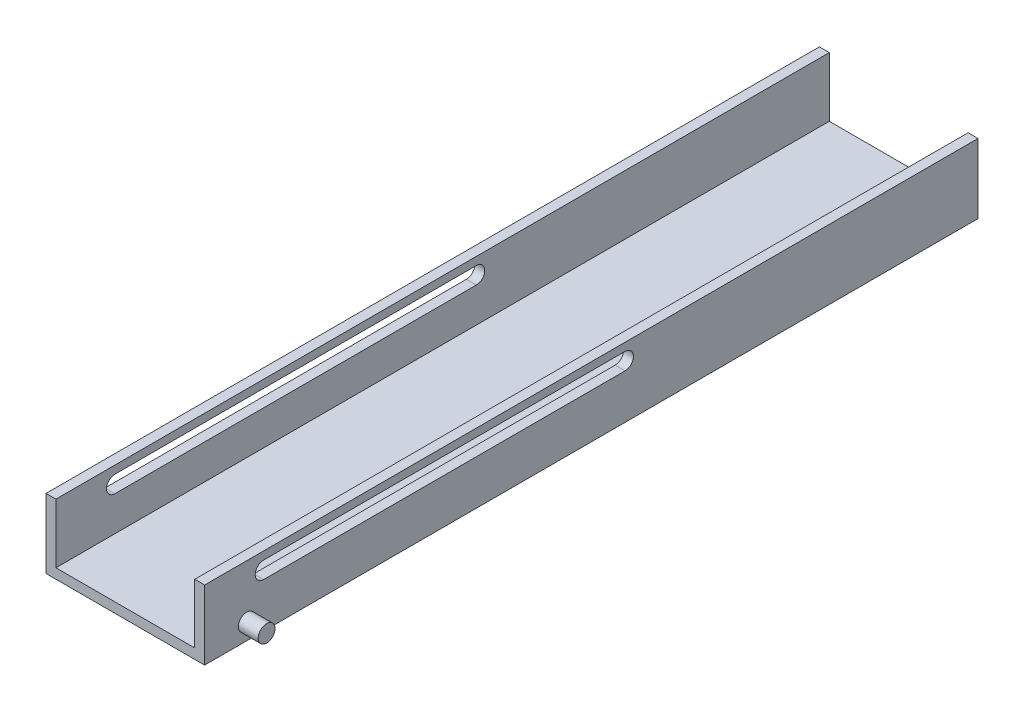
SolidWorks part; units mm, degrees
ref_plane "Front Plane" through (0, 0, 0) normal (0, 0, 1) x (1, 0, 0)
ref_plane "Top Plane" through (0, 0, 0) normal (0, 1, 0) x (1, 0, 0)
ref_plane "Right Plane" through (0, 0, 0) normal (1, 0, 0) x (0, 0, -1)
sketch "Sketch1" plane through (0, 0, 0) normal (0, 1, 0) x (1, 0, 0)
  line L1 (-20, -100) -> (20, -100)
  line L2 (-20, -100) -> (-20, 100)
  line L3 (-20, 100) -> (20, 100)
  line L4 (20, -100) -> (20, 100)
  line L5 (-20, -100) -> (20, 100) construction
  line L6 (-20, 100) -> (20, -100) construction
  point P0 (0, 0)
extrude "Boss-Extrude1" add sketch "Sketch1" along normal blind 20
sketch "Sketch2" plane through (20, 0, 0) normal (1, 0, 0) x (0, 0, -1)
  line L2 (100, 0) -> (100, 2)
  line L3 (100, 20) -> (100, 0) construction
  line L6 (100, 2) -> (100, 6.25)
  circle A2 centre (-95.75, 4.125) radius 2.125
extrude "Boss-Extrude2" add sketch "Sketch2" along normal blind 5 contours A2
sketch "Sketch3" plane through (-20, 0, 0) normal (-1, 0, 0) x (0, 0, 1)
  circle A0 centre (95.75, 4.125) radius 2.125
extrude "Boss-Extrude3" add sketch "Sketch3" along normal blind 5
sketch "Sketch4" plane through (0, 0, 100) normal (0, 0, 1) x (1, 0, 0)
  line L0 (-20, 20) -> (20, 20) construction
  line L1 (-17.5, 37.5) -> (17.5, 37.5)
  line L2 (-17.5, 37.5) -> (-17.5, 2.5)
  line L3 (-17.5, 2.5) -> (17.5, 2.5)
  line L4 (17.5, 37.5) -> (17.5, 2.5)
  line L5 (-17.5, 37.5) -> (17.5, 2.5) construction
  line L6 (-17.5, 2.5) -> (17.5, 37.5) construction
  point P0 (0, 20)
extrude "Cut-Extrude1" cut sketch "Sketch4" against normal blind 210.5
sketch "Sketch5" plane through (-20, 0, 0) normal (-1, 0, 0) x (0, 0, 1)
  line L1 (100, 0) -> (-95, 0)
  line L2 (100, 0) -> (100, 17.5)
  line L3 (100, 17.5) -> (-95, 17.5)
  line L4 (-95, 0) -> (-95, 17.5)
  line L5 (100, 0) -> (-100, 0)
  line L6 (100, 0) -> (100, 20)
  line L7 (100, 20) -> (-100, 20)
  line L8 (-100, 0) -> (-100, 20)
  line M6 (-100, 0) -> (100, 0)
  line M7 (100, 0) -> (100, 20)
  line M8 (100, 20) -> (-100, 20)
  line M9 (-100, 20) -> (-100, 0)
extrude "Cut-Extrude2" cut sketch "Sketch5" against normal blind 210.5 contours L4 L3 M6 M7 M8 M9
sketch "Sketch6" plane through (-20, 0, 0) normal (-1, 0, 0) x (0, 0, 1)
  line L5 (-90.75, 15.5) -> (95.75, 15.5)
  line L7 (-90.75, 11.25) -> (95.75, 11.25)
  arc A2 (-90.75, 15.5) -> (-90.75, 11.25) centre (-90.75, 13.375) ccw
  arc A5 (95.75, 11.25) -> (95.75, 15.5) centre (95.75, 13.375) ccw
extrude "Cut-Extrude3" cut sketch "Sketch6" against normal blind 210.5
sketch "Sketch7" plane through (-20, 0, 0) normal (-1, 0, 0) x (0, 0, 1)
  line L3 (-95, 0) -> (-95, 17.5) construction
  line L4 (6.75, 11.25) -> (-95, 11.25)
  line L6 (6.75, 15.5) -> (-95, 15.5)
  line L7 (-95, 11.25) -> (-95, 15.5)
  arc A2 (6.75, 15.5) -> (6.75, 11.25) centre (6.75, 13.375) ccw
extrude "Boss-Extrude4" add sketch "Sketch7" against normal blind 40
sketch "Sketch8" plane through (0, 0, -95) normal (0, 0, -1) x (-1, 0, 0)
  line L1 (-17.5, 11.25) -> (17.5, 11.25)
  line L2 (-17.5, 11.25) -> (-17.5, 15.5)
  line L3 (-17.5, 15.5) -> (17.5, 15.5)
  line L4 (17.5, 11.25) -> (17.5, 15.5)
extrude "Cut-Extrude4" cut sketch "Sketch8" against normal blind 141
sketch "Sketch14" plane through (-20, 0, 0) normal (-1, 0, 0) x (0, 0, 1)
  line L1 (0.375, 11.25) -> (6.75, 11.25)
  line L3 (0.375, 15.5) -> (6.75, 15.5)
  line L4 (6.75, 11.25) -> (6.75, 15.5)
  arc A3 (0.375, 15.5) -> (0.375, 11.25) centre (0.375, 13.375) ccw
extrude "Cut-Extrude5" cut sketch "Sketch14" against normal blind 50
sketch "Sketch15" plane through (-20, 0, 0) normal (-1, 0, 0) x (0, 0, 1)
  line L1 (95.75, 15.5) -> (91.5, 15.5)
  line L3 (95.75, 11.25) -> (91.5, 11.25)
  arc A0 (95.75, 11.25) -> (95.75, 15.5) centre (95.75, 13.375) ccw
  arc A2 (91.5, 11.25) -> (91.5, 15.5) centre (91.5, 13.375) ccw
extrude "Boss-Extrude5" add sketch "Sketch15" against normal blind 40
sketch "Sketch16" plane through (0, 0, 100) normal (0, 0, 1) x (1, 0, 0)
  line L1 (-17.5, 11.25) -> (17.5, 11.25)
  line L2 (-17.5, 11.25) -> (-17.5, 15.5)
  line L3 (-17.5, 15.5) -> (17.5, 15.5)
  line L4 (17.5, 11.25) -> (17.5, 15.5)
extrude "Cut-Extrude6" cut sketch "Sketch16" against normal blind 40
sketch "Sketch17" plane through (-20, 0, 0) normal (-1, 0, 0) x (0, 0, 1)
  line L0 (-95, 0) -> (100, 0) construction
  line L1 (-95, 17.5) -> (-88.625, 17.5)
  line L2 (-95, 17.5) -> (-95, 0)
  line L3 (-95, 0) -> (-88.625, 0)
  line L4 (-88.625, 17.5) -> (-88.625, 0)
extrude "Cut-Extrude7" cut sketch "Sketch17" against normal blind 53
sketch "Sketch18" plane through (0, 0, 100) normal (0, 0, 1) x (1, 0, 0)
  line L0 (-20, 17.5) -> (-17.5, 17.5)
  line L1 (-17.5, 17.5) -> (-17.5, 2.5) construction
  line L2 (-17.5, 17.5) -> (-17.5, 2.5)
  line L3 (-17.5, 2.5) -> (17.5, 2.5)
  line L4 (17.5, 2.5) -> (17.5, 17.5)
  line L5 (17.5, 17.5) -> (20, 17.5)
  line L6 (20, 17.5) -> (20, 0)
  line L7 (20, 0) -> (-20, 0)
  line L8 (-20, 0) -> (-20, 17.5)
extrude "Boss-Extrude6" add sketch "Sketch18" along normal blind 6.375
